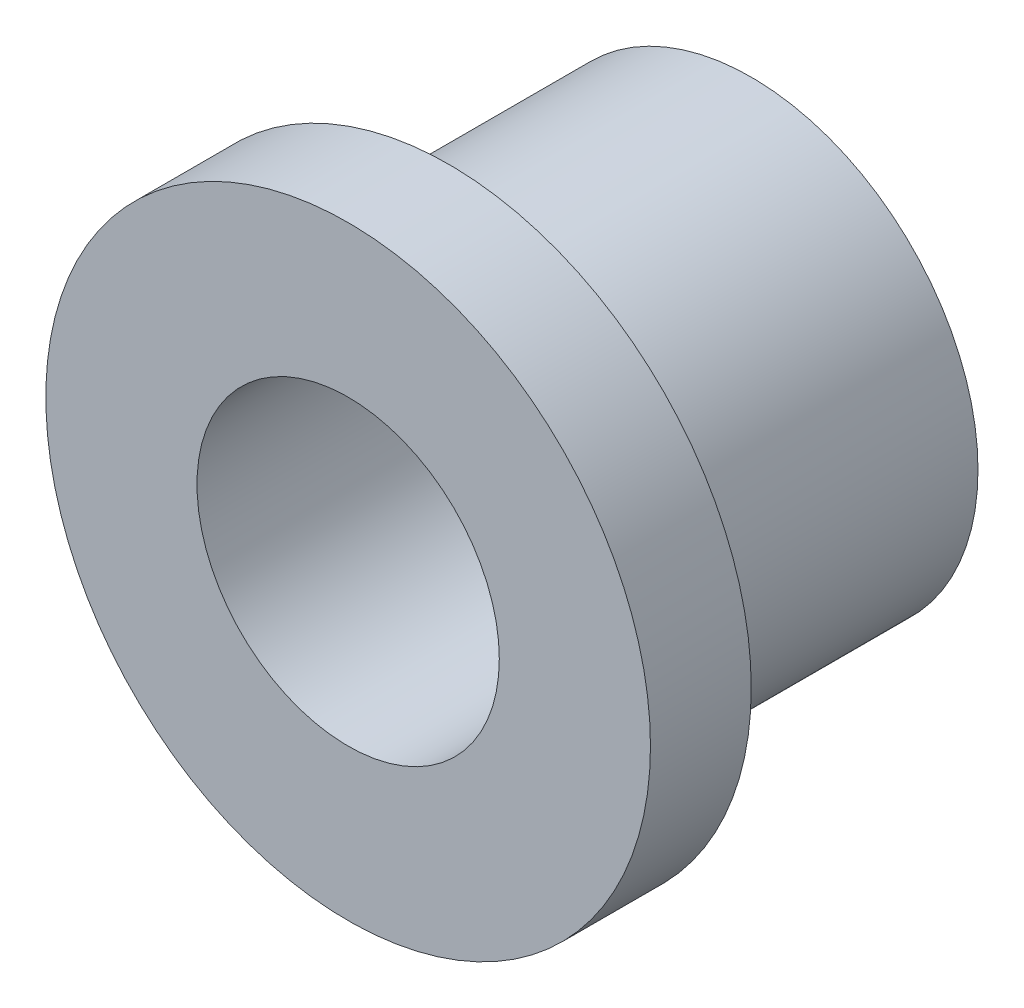
SolidWorks part; units mm, degrees
ref_plane "Front Plane" through (0, 0, 0) normal (0, 0, 1) x (1, 0, 0)
ref_plane "Top Plane" through (0, 0, 0) normal (0, 1, 0) x (1, 0, 0)
ref_plane "Right Plane" through (0, 0, 0) normal (1, 0, 0) x (0, 0, -1)
sketch "Sketch1" plane through (0, 0, 0) normal (0, 0, 1) x (1, 0, 0)
  circle A0 centre (0, 0) radius 3
  circle A1 centre (0, 0) radius 4.5
  dimension "D1" = 6
  dimension "D2" = 9
extrude "Boss-Extrude1" add sketch "Sketch1" along normal blind 8
sketch "Sketch2" plane through (0, 0, 8) normal (0, 0, 1) x (1, 0, 0)
  circle A0 centre (0, 0) radius 6
  circle A1 centre (0, 0) radius 4.5 construction
  circle A2 centre (0, 0) radius 4.5
  dimension "D1" = 12
extrude "Boss-Extrude2" add sketch "Sketch2" against normal blind 2
